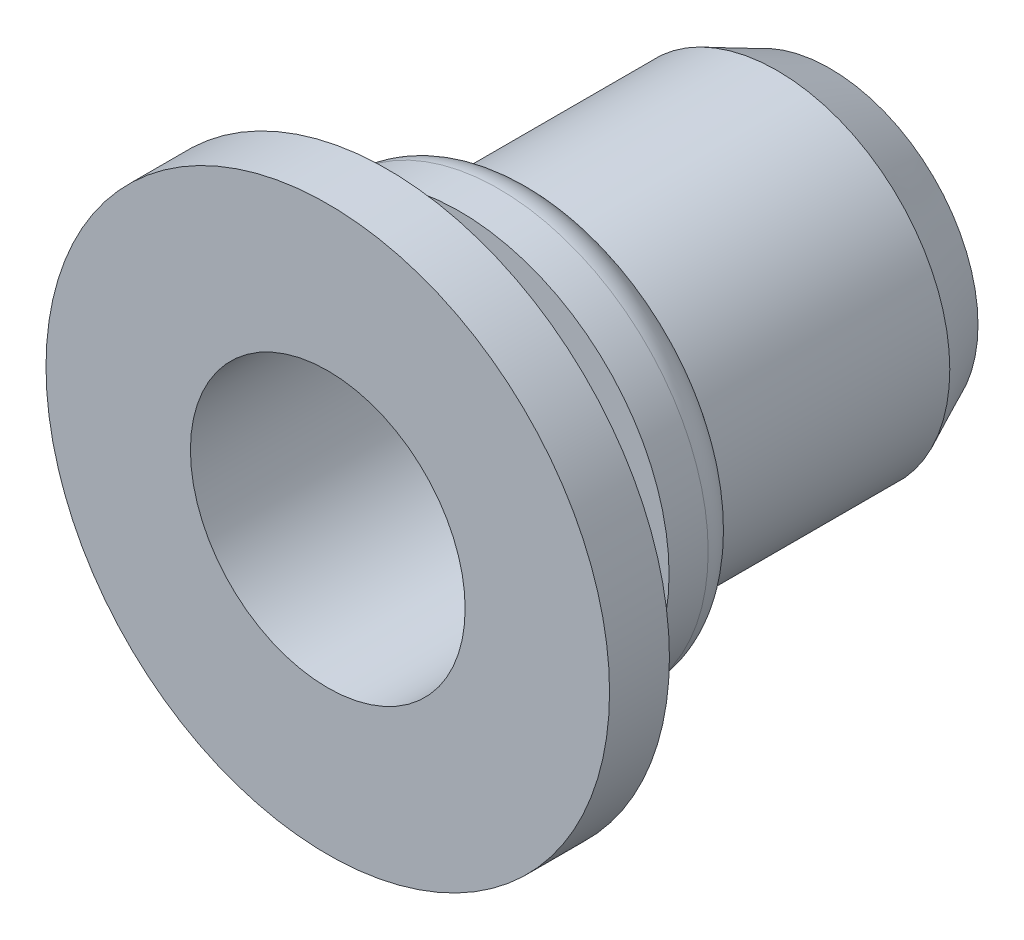
SolidWorks part; units mm, degrees
ref_plane "Front Plane" through (0, 0, 0) normal (0, 0, 1) x (1, 0, 0)
ref_plane "Top Plane" through (0, 0, 0) normal (0, 1, 0) x (1, 0, 0)
ref_plane "Right Plane" through (0, 0, 0) normal (1, 0, 0) x (0, 0, -1)
sketch "Sketch1" plane through (0, 0, 0) normal (1, 0, 0) x (0, 0, -1)
  line L0 (0, 0) -> (6.5837, 0) construction
  line L1 (0, 0) -> (0, 1.95) construction
  line L2 (-0.85, 1.95) -> (2.03, 1.95)
  line L3 (2.03, 1.95) -> (2.03, 1.5)
  line L4 (-0.85, 1.95) -> (-0.85, 4)
  line L5 (-0.85, 4) -> (0, 4)
  line L6 (0, 4) -> (0, 2.45)
  line L7 (0, 2.45) -> (1.02, 2.45)
  line L8 (1.02, 2.45) -> (1.02, 2.975)
  line L10 (2.1, 2.45) -> (5.53, 2.45)
  line L11 (5.53, 2.45) -> (6.28, 2.1003)
  line L12 (6.28, 2.1003) -> (6.28, 1.5)
  line L13 (6.28, 1.5) -> (6.1238, 1.2295)
  line L14 (6.1238, 1.2295) -> (2.1862, 1.2295)
  line L15 (2.1862, 1.2295) -> (2.03, 1.5)
  line L16 (1.02, 2.975) -> (1.575, 2.975)
  arc A1 (1.575, 2.975) -> (2.1, 2.45) centre (1.575, 2.45) cw
  dimension "D1" = 8
  dimension "D2" = 0.85
  dimension "D3" = 4.9
  dimension "D4" = 1.02
  dimension "D6" = 5.95
  dimension "D5" = 1.08
  dimension "D7" = 2.459
  dimension "D8" = 7.13
  dimension "D9" = 0.75
  dimension "D10" = 3
  dimension "D11" = 60
  dimension "D12" = 25
  dimension "D13" = 30
  dimension "D14" = 2.88
  dimension "D15" = 3.9
  dimension "D16" = 3
revolve "Revolve1" add sketch "Sketch1" angle 360 about L0
equation "\"D8@Sketch1\"=9-\"D2@Sketch1\"-\"D4@Sketch1\""
equation "\"D14@Sketch1\"=3.9-\"D4@Sketch1\""
